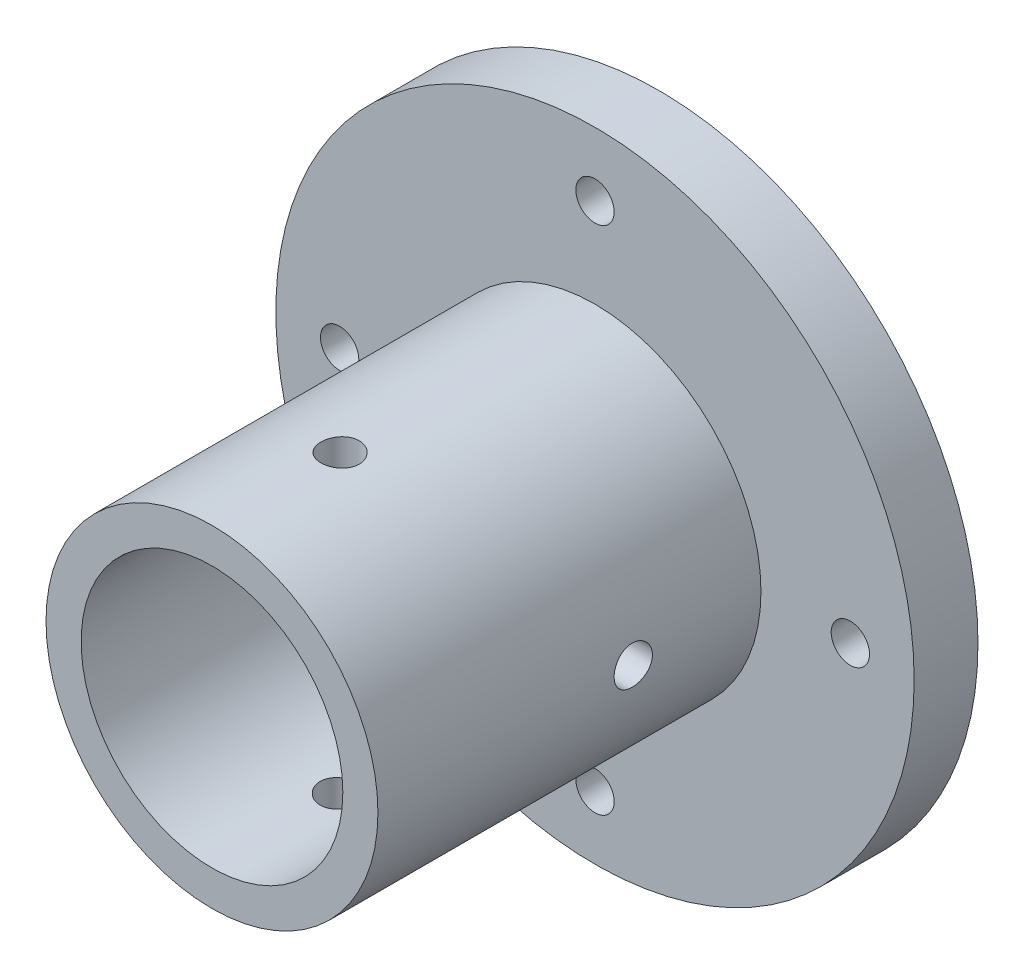
SolidWorks part; units mm, degrees
ref_plane "Plan de face" through (0, 0, 0) normal (0, 0, 1) x (1, 0, 0)
ref_plane "Plan de dessus" through (0, 0, 0) normal (0, 1, 0) x (1, 0, 0)
ref_plane "Plan de droite" through (0, 0, 0) normal (1, 0, 0) x (0, 0, -1)
sketch "Esquisse1" plane through (0, 0, 0) normal (0, 0, 1) x (1, 0, 0)
  circle A0 centre (0, 0) radius 25
  dimension "D1" = 50
extrude "Boss.-Extru.1" add sketch "Esquisse1" along normal blind 5
sketch "Esquisse2" plane through (0, 0, 5) normal (0, 0, 1) x (1, 0, 0)
  circle A0 centre (0, 0) radius 13
  circle A1 centre (0, 0) radius 10.25
  dimension "D1" = 20.5
  dimension "D2" = 26
extrude "Boss.-Extru.2" add sketch "Esquisse2" along normal blind 30
sketch "Esquisse3" plane through (0, 0, 5) normal (0, 0, 1) x (1, 0, 0)
  circle A0 centre (0, 0) radius 20 construction
  circle A1 centre (0, 20) radius 1.5
  dimension "D1" = 40
  dimension "D2" = 3
extrude "Enlèv. mat.-Extru.1" cut sketch "Esquisse3" against normal through all
pattern_circular "Répétition circulaire1" count 4 every 90 about axis through (0, 0, 0) along (0, 0, 1) of "Enlèv. mat.-Extru.1"
hole_wizard "Diamètre du perçage Ø3.0 (3)1" positions "Esquisse3D1" profile "Esquisse4" hole size "Ø3.0" standard "ISO" end condition through all
sketch3d "Esquisse3D1"
  point P17 (-0.0331, -13, 25)
  point P19 (-13, 0.0337, 15)
  dimension "D1" = 10
  dimension "D2" = 20
sketch "Esquisse4" plane through (-0.0331, -13, 25) normal (0, 0, 1) x (1, -0.0025, 0)
  line L0 (0, 0) -> (0, 38.0637)
  line L1 (0, 38.0637) -> (1.5, 38.0637)
  line L2 (1.5, 38.0637) -> (1.5, 0)
  line L5 (1.5, 0) -> (0, 0)
  line L11 (0, -6.35) -> (0, 107.95) construction
  dimension "Diamètre du perçage jusqu'au prochain" = 3
  dimension "Profondeur du perçage jusqu'au prochain" = 38.0637
